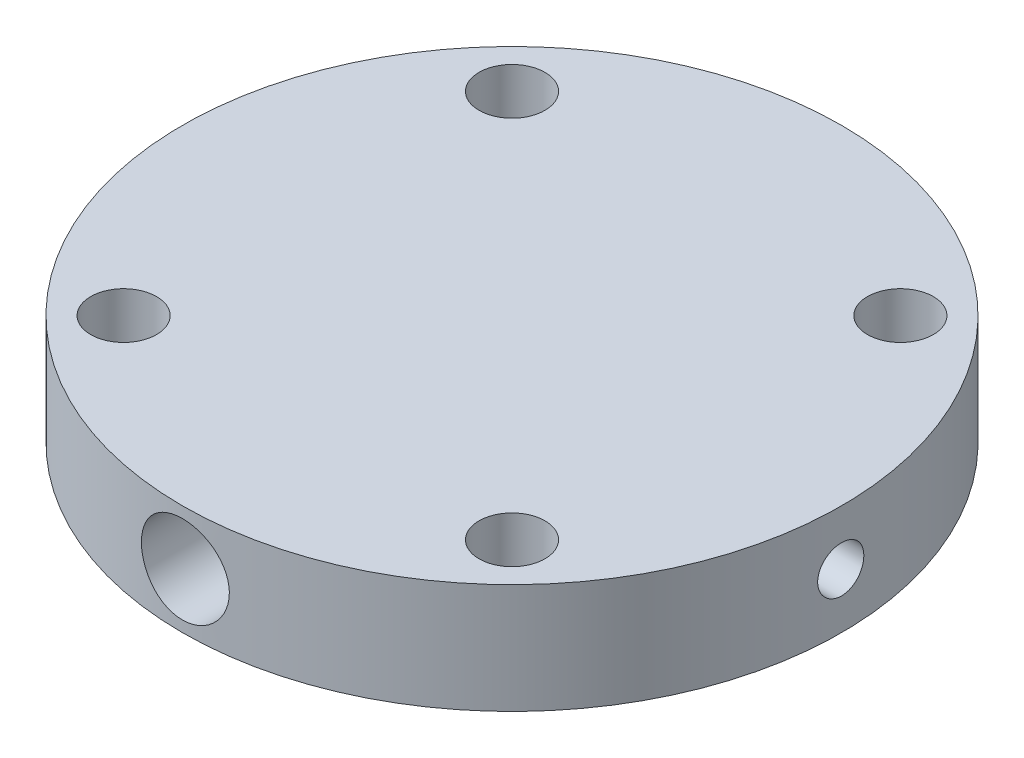
SolidWorks part; units mm, degrees
ref_plane "前视基准面" through (0, 0, 0) normal (0, 0, 1) x (1, 0, 0)
ref_plane "上视基准面" through (0, 0, 0) normal (0, 1, 0) x (1, 0, 0)
ref_plane "右视基准面" through (0, 0, 0) normal (1, 0, 0) x (0, 0, -1)
sketch "草图1" plane through (0, 0, 0) normal (0, 1, 0) x (1, 0, 0)
  line L0 (-54.9285, 0) -> (63.5937, 0) construction
  line L1 (0, 72.3324) -> (0, -49.8616) construction
  line L2 (-41.0148, 41.0148) -> (0, 0) construction
  circle A0 centre (0, 0) radius 30
  circle A1 centre (0, 0) radius 25 construction
  circle A2 centre (-17.6777, 17.6777) radius 3
  circle A3 centre (17.6777, 17.6777) radius 3
  circle A4 centre (17.6777, -17.6777) radius 3
  circle A5 centre (-17.6777, -17.6777) radius 3
  dimension "D1" = 50
  dimension "D2" = 60
  dimension "D4" = 6
  dimension "D3" = 45
extrude "凸台-拉伸1" add sketch "草图1" along normal blind 10
sketch "草图2" plane through (0, 0, 0) normal (0, 0, 1) x (1, 0, 0)
  line L0 (-30, 0) -> (30, 0) construction
  circle A0 centre (0, 5) radius 4
  dimension "D2" = 8
  dimension "D1" = 5
extrude "切除-拉伸1" cut sketch "草图2" against normal through all both and the other way through all
sketch "草图3" plane through (0, 0, 0) normal (1, 0, 0) x (0, 0, -1)
  line L0 (0, 0) -> (0, 10) construction
  line L1 (-30, 0) -> (30, 0) construction
  line L2 (30, 10) -> (-30, 10) construction
  line L3 (0, 5) -> (-37.8651, 5) construction
  circle A0 centre (0, 5) radius 2
  dimension "D1" = 4
extrude "凸台-拉伸2" add sketch "草图3" along normal mid plane 65
hole_wizard "M5 螺纹孔2" positions "草图9" profile "草图10" tap size "M5" standard "GB" end condition through all
sketch "草图9" plane through (32.5, 0, 0) normal (1, 0, 0) x (0, 0, -1)
  point P0 (0, 5)
sketch "草图10" plane through (32.5, 5, 0) normal (0, 1, 0) x (0, 0, -1)
  line L0 (0, 0) -> (0, 65)
  line L1 (0, 65) -> (2.1, 65)
  line L2 (2.1, 65) -> (2.1, 0)
  line L5 (2.1, 0) -> (0, 0)
  line L11 (0, -6.35) -> (0, 107.95) construction
  dimension "通孔螺纹孔钻头直径" = 4.2
  dimension "通孔螺纹孔钻头深度" = 65
cosmetic thread "孔螺蚊线2" parameters "D2"=5
